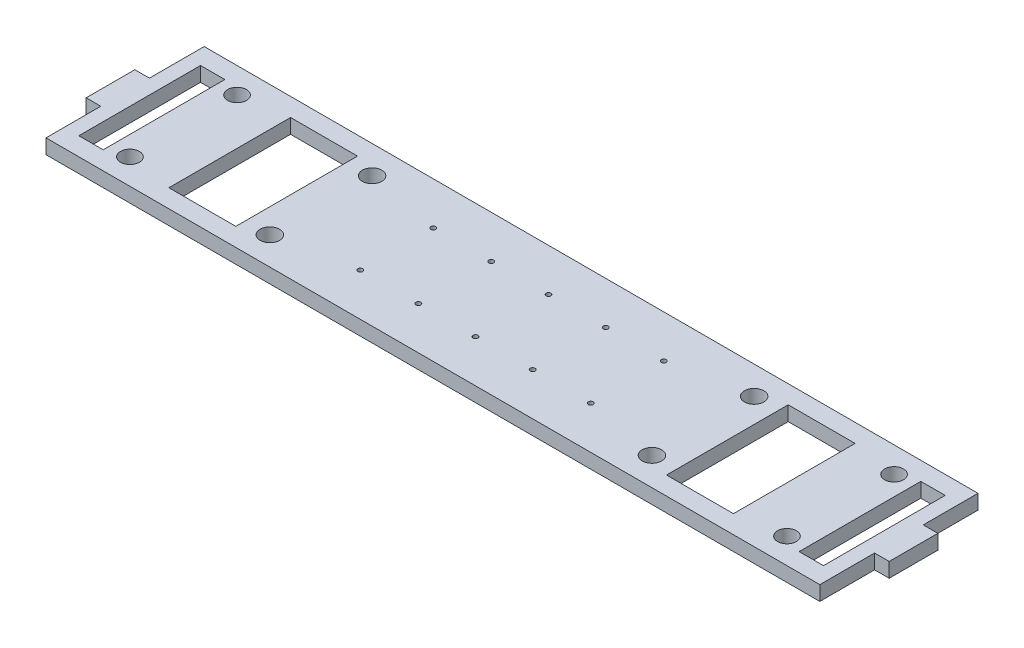
SolidWorks part; units mm, degrees
ref_plane "Plan de face" through (0, 0, 0) normal (0, 0, 1) x (1, 0, 0)
ref_plane "Plan de dessus" through (0, 0, 0) normal (0, 1, 0) x (1, 0, 0)
ref_plane "Plan de droite" through (0, 0, 0) normal (1, 0, 0) x (0, 0, -1)
sketch "Esquisse1" plane through (0, 0, 0) normal (0, 1, 0) x (1, 0, 0)
  line L0 (-159, -32.5) -> (-159, -10)
  line L1 (-159, 32.5) -> (159, 32.5)
  line L2 (-165, -10) -> (-165, 10)
  line L3 (-159, -32.5) -> (159, -32.5)
  line L4 (-159, -32.5) -> (159, 32.5) construction
  line L5 (159, -32.5) -> (159, -10)
  line L6 (159, -10) -> (165, -10)
  line L7 (-159, -10) -> (-165, -10)
  line L8 (-165, 10) -> (-159, 10)
  line L9 (-159, 10) -> (-159, 32.5)
  line L10 (165, -10) -> (165, 10)
  line L11 (165, 10) -> (159, 10)
  line L12 (159, 10) -> (159, 32.5)
  line L13 (159, 32.5) -> (159.1702, 32.352) construction
  line L14 (165, 0) -> (-165, 0) construction
  point P0 (0, 0)
  dimension "D1" = 330
  dimension "D2" = 6
  dimension "D3" = 6
  dimension "D4" = 6
  dimension "D5" = 6
  dimension "D6" = 65
  dimension "D7" = 20
  dimension "D8" = 20
extrude "Boss.-Extru.1" add sketch "Esquisse1" along normal blind 6 contours L3 L5 L6 L10 L11 L12 L1 L9 L8 L2 L7 L0
sketch "Esquisse2" plane through (0, 0, 0) normal (0, -1, 0) x (1, 0, 0)
  line L0 (-47.35, 0) -> (47.35, 0) construction
  line L1 (0, 32.5) -> (0, -32.5) construction
  line L2 (-47.35, 15) -> (47.35, 15) construction
  line L3 (159, 32.5) -> (-159, 32.5) construction
  line L4 (-159, -32.5) -> (159, -32.5) construction
  circle A0 centre (-47.35, 15) radius 1.005
  circle A1 centre (-23.5, 15) radius 1.005
  circle A2 centre (23.5, 15) radius 1.005
  circle A3 centre (47.35, 15) radius 1.005
  circle A4 centre (47.35, -15) radius 1.005
  circle A5 centre (23.5, -15) radius 1.005
  circle A6 centre (-23.5, -15) radius 1.005
  circle A7 centre (-47.35, -15) radius 1.005
  circle A8 centre (0, 15) radius 1.005
  circle A9 centre (0, -15) radius 1.005
  dimension "D1" = 2.01
  dimension "D2" = 2.01
  dimension "D5" = 2.01
  dimension "D3" = 23.5
  dimension "D4" = 15
  dimension "D6" = 23.85
extrude "Enlèv. mat.-Extru.1" cut sketch "Esquisse2" against normal through all
sketch "Esquisse3" plane through (0, 0, 0) normal (0, -1, 0) x (-1, 0, 0)
  line L0 (0, -32.5) -> (0, 32.5) construction
  line L1 (159, -32.5) -> (-159, -32.5) construction
  line L2 (159, 32.5) -> (-159, 32.5) construction
  line L3 (165, 0) -> (-165, 0) construction
  line L4 (165, -10) -> (165, 10) construction
  line L5 (-165, -10) -> (-165, 10) construction
  circle A0 centre (47.35, -15) radius 3
  circle A1 centre (23.5, -15) radius 3
  circle A2 centre (0, -15) radius 3
  circle A3 centre (0, 15) radius 3
  circle A4 centre (23.5, 15) radius 3
  circle A5 centre (47.35, 15) radius 3
  circle A6 centre (-47.35, 15) radius 3
  circle A7 centre (-23.5, 15) radius 3
  circle A8 centre (-23.5, -15) radius 3
  circle A9 centre (-47.35, -15) radius 3
  dimension "D1" = 6
  dimension "D2" = 6
  dimension "D3" = 6
extrude "Enlèv. mat.-Extru.2" cut sketch "Esquisse3" against normal blind 3
sketch "Esquisse4" plane through (0, 0, 0) normal (0, -1, 0) x (-1, 0, 0)
  line L0 (165, 0) -> (-165, 0) construction
  line L1 (165, -10) -> (165, 10) construction
  line L2 (-165, -10) -> (-165, 10) construction
  line L4 (159, -32.5) -> (-159, -32.5) construction
  line L5 (0, -32.5) -> (0, 32.5) construction
  line L6 (159, 32.5) -> (-159, 32.5) construction
  circle A0 centre (78.5, -21) radius 4
  circle A1 centre (-78.5, -21) radius 4
  circle A2 centre (78.5, 21) radius 4
  circle A3 centre (-78.5, 21) radius 4
  dimension "D1" = 21
  dimension "D2" = 8
  dimension "D3" = 78.5
extrude "Enlèv. mat.-Extru.3" cut sketch "Esquisse4" against normal through all
sketch "Esquisse5" plane through (0, 0, 0) normal (0, -1, 0) x (-1, 0, 0)
  line L0 (0, -32.5) -> (0, 32.5) construction
  line L1 (159, -32.5) -> (-159, -32.5) construction
  line L2 (159, 32.5) -> (-159, 32.5) construction
  line L3 (-116, 25) -> (-88.5, -25) construction
  line L4 (116, -25) -> (88.5, -25)
  line L5 (116, -25) -> (116, 25)
  line L6 (116, 25) -> (88.5, 25)
  line L7 (88.5, -25) -> (88.5, 25)
  line L8 (116, -25) -> (88.5, 25) construction
  line L9 (116, 25) -> (88.5, -25) construction
  line L10 (-116, -25) -> (-88.5, 25) construction
  line L11 (-88.5, -25) -> (-88.5, 25)
  line L12 (-116, 25) -> (-88.5, 25)
  line L13 (-116, -25) -> (-116, 25)
  line L14 (-116, -25) -> (-88.5, -25)
  point P6 (102.25, 0)
  point P16 (-102.25, 0)
  dimension "D1" = 88.5
  dimension "D2" = 27.5
  dimension "D3" = 50
extrude "Enlèv. mat.-Extru.4" cut sketch "Esquisse5" against normal through all
sketch "Esquisse6" plane through (0, 0, 0) normal (0, -1, 0) x (-1, 0, 0)
  line L0 (0, -32.5) -> (0, 32.5) construction
  line L1 (159, -32.5) -> (-159, -32.5) construction
  line L2 (159, 32.5) -> (-159, 32.5) construction
  line L4 (-165, -10) -> (-165, 10) construction
  line L5 (-165, 0) -> (165, 0) construction
  line L6 (165, -10) -> (165, 10) construction
  circle A0 centre (135, -22) radius 3.875
  circle A1 centre (-135, -22) radius 3.875
  circle A2 centre (-135, 22) radius 3.875
  circle A3 centre (135, 22) radius 3.875
  dimension "D1" = 7.75
  dimension "D2" = 135
  dimension "D3" = 22
extrude "Enlèv. mat.-Extru.5" cut sketch "Esquisse6" against normal through all
sketch "Esquisse7" plane through (0, 0, 0) normal (0, -1, 0) x (-1, 0, 0)
  line L0 (0, -32.5) -> (0, 32.5) construction
  line L1 (153, -25) -> (143, -25)
  line L2 (153, -25) -> (153, 25)
  line L3 (153, 25) -> (143, 25)
  line L4 (143, -25) -> (143, 25)
  line L5 (153, -25) -> (143, 25) construction
  line L6 (153, 25) -> (143, -25) construction
  line L7 (159, -32.5) -> (-159, -32.5) construction
  line L8 (159, 32.5) -> (-159, 32.5) construction
  line L9 (-153, 25) -> (-143, -25) construction
  line L10 (-153, -25) -> (-143, 25) construction
  line L11 (-143, -25) -> (-143, 25)
  line L12 (-153, 25) -> (-143, 25)
  line L13 (-153, -25) -> (-153, 25)
  line L14 (-153, -25) -> (-143, -25)
  point P0 (148, 0)
  point P16 (-148, 0)
  dimension "D1" = 143
  dimension "D2" = 10
  dimension "D3" = 50
extrude "Enlèv. mat.-Extru.6" cut sketch "Esquisse7" against normal through all
